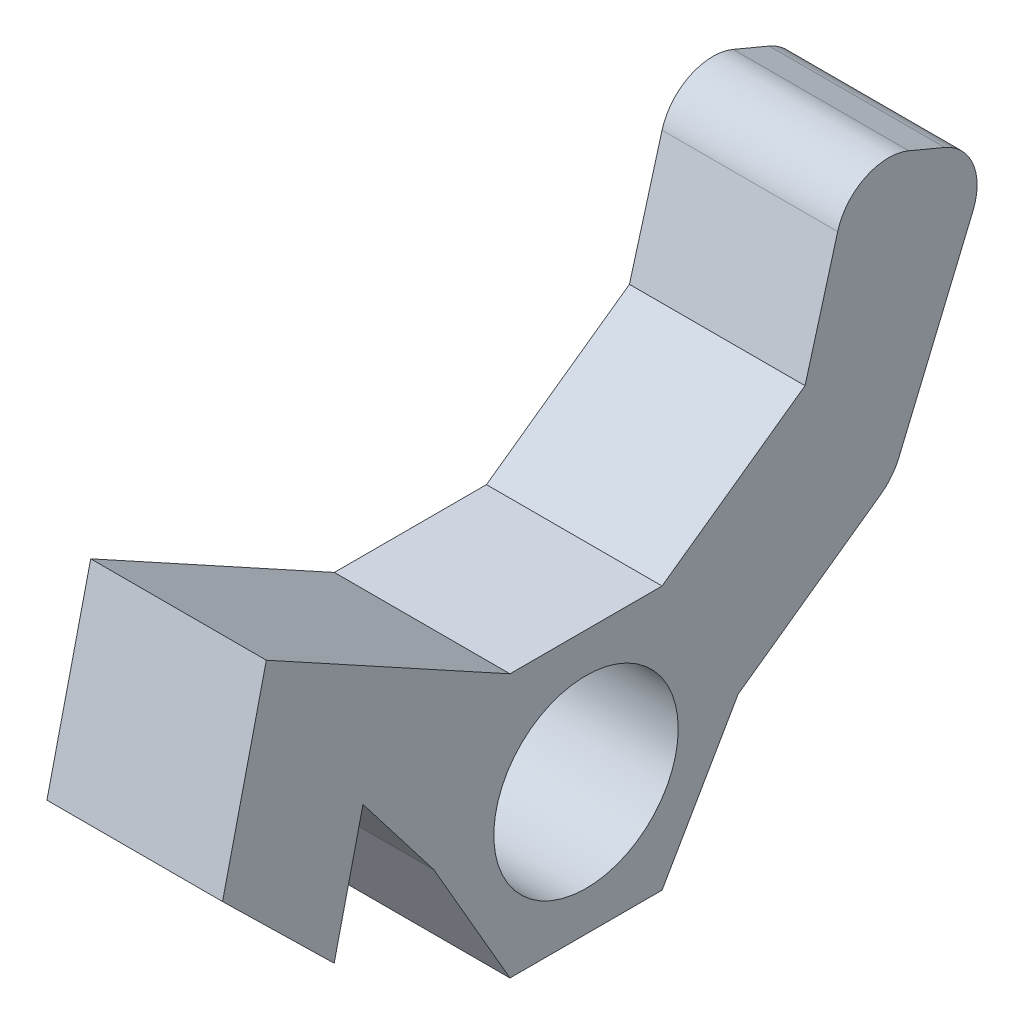
SolidWorks part; units mm, degrees
ref_plane "Alzado" through (0, 0, 0) normal (0, 0, 1) x (1, 0, 0)
ref_plane "Planta" through (0, 0, 0) normal (0, 1, 0) x (1, 0, 0)
ref_plane "Vista lateral" through (0, 0, 0) normal (1, 0, 0) x (0, 0, -1)
sketch "Croquis1" plane through (0, 0, 0) normal (1, 0, 0) x (0, 0, -1)
  line L1 (3.4641, 0) -> (1.7321, 3)
  line L2 (1.7321, 3) -> (-1.7321, 3)
  line L3 (-1.7321, 3) -> (-3.4641, 0)
  line L4 (-3.4641, 0) -> (-1.7321, -3)
  line L5 (-1.7321, -3) -> (1.7321, -3)
  line L6 (1.7321, -3) -> (3.4641, 0)
  circle A0 centre (0, 0) radius 2.1
  circle A1 centre (0, 0) radius 3 construction
  dimension "D1" = 4.2
  dimension "D2" = 6
extrude "Saliente-Extruir1" add sketch "Croquis1" along normal blind 4
sketch "Croquis2" plane through (4, 0, 0) normal (1, 0, 0) x (0, 0, -1)
  line L0 (1.7321, 3) -> (4.9887, 5.3226)
  line L1 (4.9887, 5.3226) -> (6.9908, 2.5153)
  line L2 (6.9908, 2.5153) -> (3.4641, 0)
  line L3 (1.7321, 3) -> (3.4641, 0)
  line L9 (1.7321, -3) -> (3.4641, 0)
  line L10 (3.4641, 0) -> (1.7321, 3)
  line L11 (1.7321, 3) -> (-1.7321, 3)
  line L12 (-1.7321, 3) -> (-3.4641, 0)
  line L13 (-3.4641, 0) -> (-1.7321, -3)
  line L14 (-1.7321, -3) -> (1.7321, -3)
  line L15 (1.7321, -3) -> (3.4641, 0)
  line L17 (1.7321, 3) -> (-1.7321, 3)
  line L18 (-1.7321, 3) -> (-3.4641, 0)
  line L19 (-3.4641, 0) -> (-1.7321, -3)
  line L20 (-1.7321, -3) -> (1.7321, -3)
  line M9 (3.4641, 0) -> (1.7321, 3)
  dimension "D2" = 0
extrude "Saliente-Extruir2" add sketch "Croquis2" against normal through all contours L2 L1 L0 M9
sketch "Croquis12" plane through (4, 0, 0) normal (1, 0, 0) x (0, 0, -1)
  line L0 (-3.4641, 0) -> (-5.08, 2.0976)
  line L1 (-5.08, 2.0976) -> (-5.7362, -0.7064)
  line L2 (-5.7362, -0.7064) -> (-8.2788, 1.7808)
  line L3 (-8.2788, 1.7808) -> (-7.2813, 6.0431)
  line L4 (-7.2813, 6.0431) -> (-1.7321, 3)
  line L5 (-3.4641, 0) -> (-1.7321, 3)
  line L13 (6.9908, 2.5153) -> (4.9887, 5.3226)
  line L14 (4.9887, 5.3226) -> (1.7321, 3)
  line L15 (1.7321, 3) -> (-1.7321, 3)
  line L16 (-1.7321, 3) -> (-3.4641, 0)
  line L17 (-3.4641, 0) -> (-1.7321, -3)
  line L18 (-1.7321, -3) -> (1.7321, -3)
  line L19 (1.7321, -3) -> (3.4641, 0)
  line L20 (3.4641, 0) -> (6.9908, 2.5153)
  line L21 (6.9908, 2.5153) -> (4.9887, 5.3226)
  line L22 (4.9887, 5.3226) -> (1.7321, 3)
  line L23 (1.7321, 3) -> (-1.7321, 3)
  line L25 (-3.4641, 0) -> (-1.7321, -3)
  line L26 (-1.7321, -3) -> (1.7321, -3)
  line L27 (1.7321, -3) -> (3.4641, 0)
  line L28 (3.4641, 0) -> (6.9908, 2.5153)
  line M15 (-1.7321, 3) -> (-3.4641, 0)
  dimension "D1" = 0
extrude "Saliente-Extruir3" add sketch "Croquis12" against normal through all contours L4 L3 L2 L1 L0 M15
sketch "Croquis13" plane through (4, 0, 0) normal (1, 0, 0) x (0, 0, -1)
  line L0 (6.9908, 2.5153) -> (9.2787, 7.9662)
  line L1 (9.2787, 7.9662) -> (6.0976, 9.3014)
  line L2 (6.0976, 9.3014) -> (4.9887, 5.3226)
  line L3 (4.9887, 5.3226) -> (6.9908, 2.5153)
  dimension "D1" = 3.4482
  dimension "D2" = 3.45
extrude "Saliente-Extruir4" add sketch "Croquis13" against normal through all
fillet "Redondeo1" radius 1.2 3 edges at (2, 2.5153, -6.9908) (2, 7.9662, -9.2787) (2, 9.3014, -6.0976)
